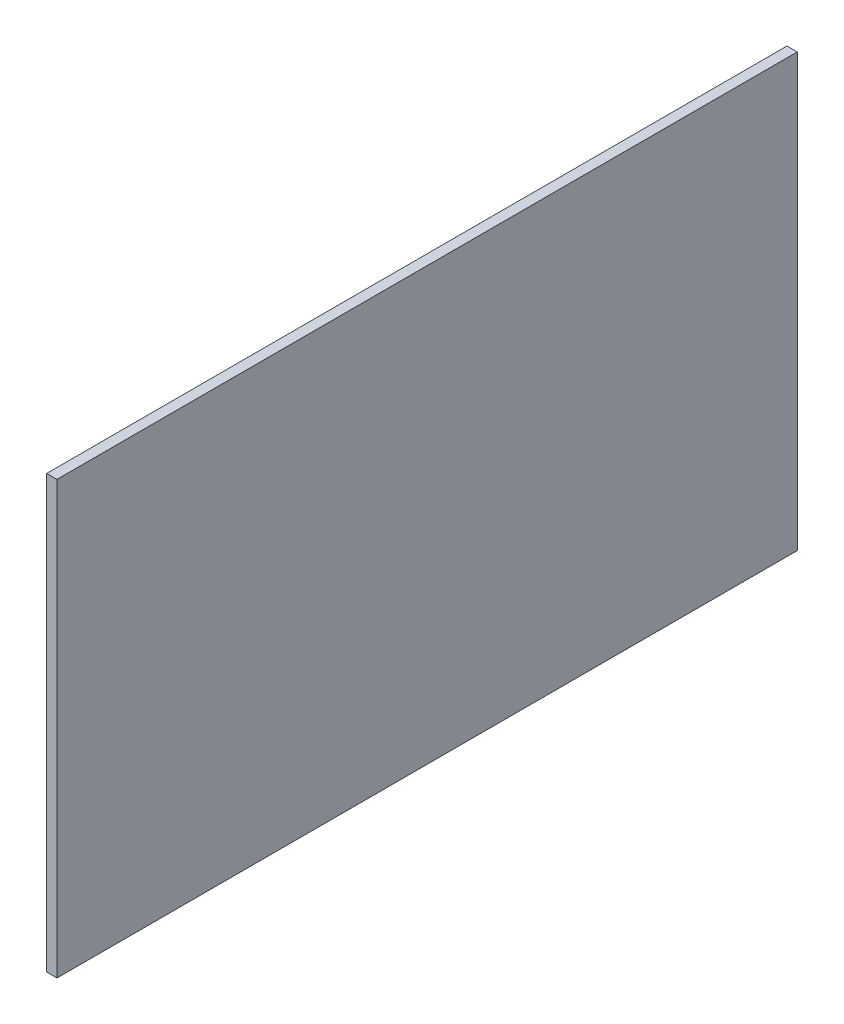
SolidWorks part; units mm, degrees
material "Acrylic (Medium-high impact)"
ref_plane "X-Y Datum" through (0, 0, 0) normal (0, 0, 1) x (1, 0, 0)
ref_plane "X-Z Datum" through (0, 0, 0) normal (0, 1, 0) x (1, 0, 0)
ref_plane "Y-Z Datum" through (0, 0, 0) normal (1, 0, 0) x (0, 0, -1)
sketch "Sketch1" plane through (0, 0, 0) normal (1, 0, 0) x (0, 0, -1)
  line L1 (-57.15, 33.3375) -> (57.15, 33.3375)
  line L2 (-57.15, 33.3375) -> (-57.15, -33.3375)
  line L3 (-57.15, -33.3375) -> (57.15, -33.3375)
  line L4 (57.15, 33.3375) -> (57.15, -33.3375)
  line L5 (-57.15, 33.3375) -> (57.15, -33.3375) construction
  line L6 (-57.15, -33.3375) -> (57.15, 33.3375) construction
  point P0 (0, 0)
  dimension "D1" = 114.3
  dimension "D2" = 66.675
extrude "Boss-Extrude1" add sketch "Sketch1" along normal blind 1.5875
